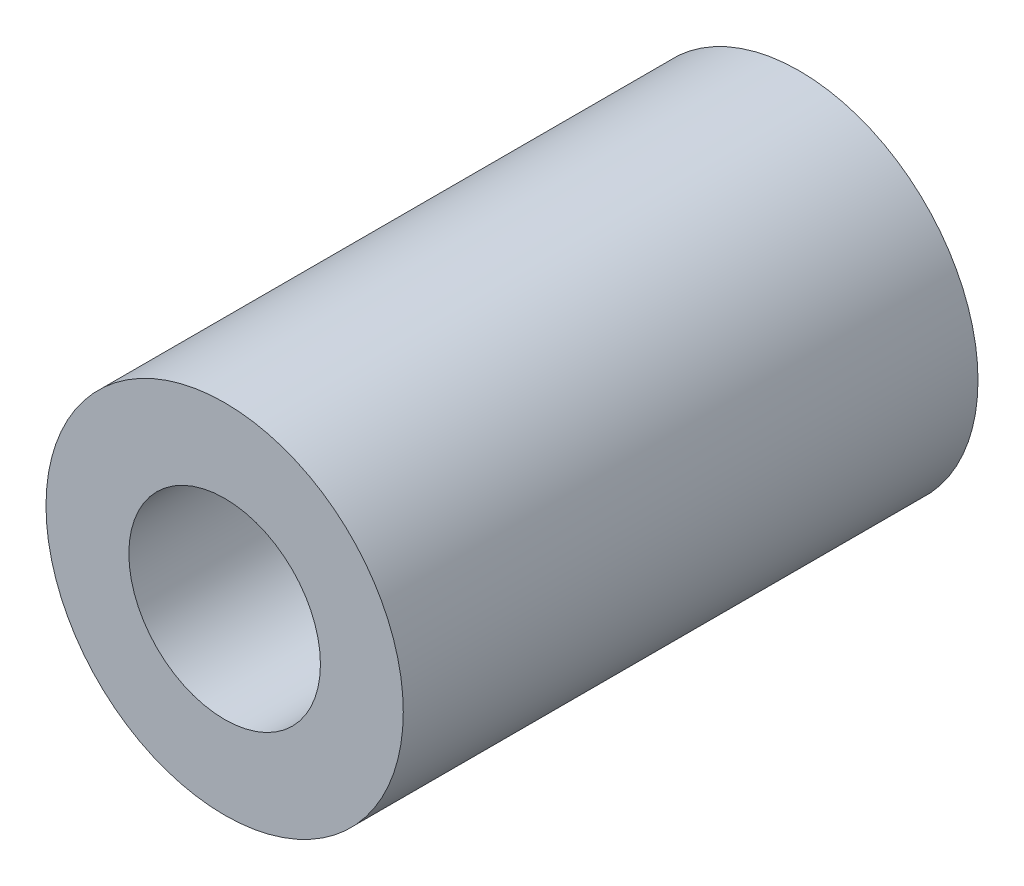
SolidWorks part; units mm, degrees
ref_plane "Front Plane" through (0, 0, 0) normal (0, 0, 1) x (1, 0, 0)
ref_plane "Top Plane" through (0, 0, 0) normal (0, 1, 0) x (1, 0, 0)
ref_plane "Right Plane" through (0, 0, 0) normal (1, 0, 0) x (0, 0, -1)
sketch "Sketch1" plane through (0, 0, 0) normal (0, 0, 1) x (1, 0, 0)
  circle A0 centre (0, 0) radius 7.46
  dimension "D1" = 14.92
extrude "Boss-Extrude1" add sketch "Sketch1" along normal blind 24
sketch "Sketch2" plane through (0, 0, 0) normal (0, 0, 1) x (1, 0, 0)
  circle A0 centre (0, 0) radius 4
  dimension "D1" = 8
extrude "Cut-Extrude1" cut sketch "Sketch2" along normal blind 24
